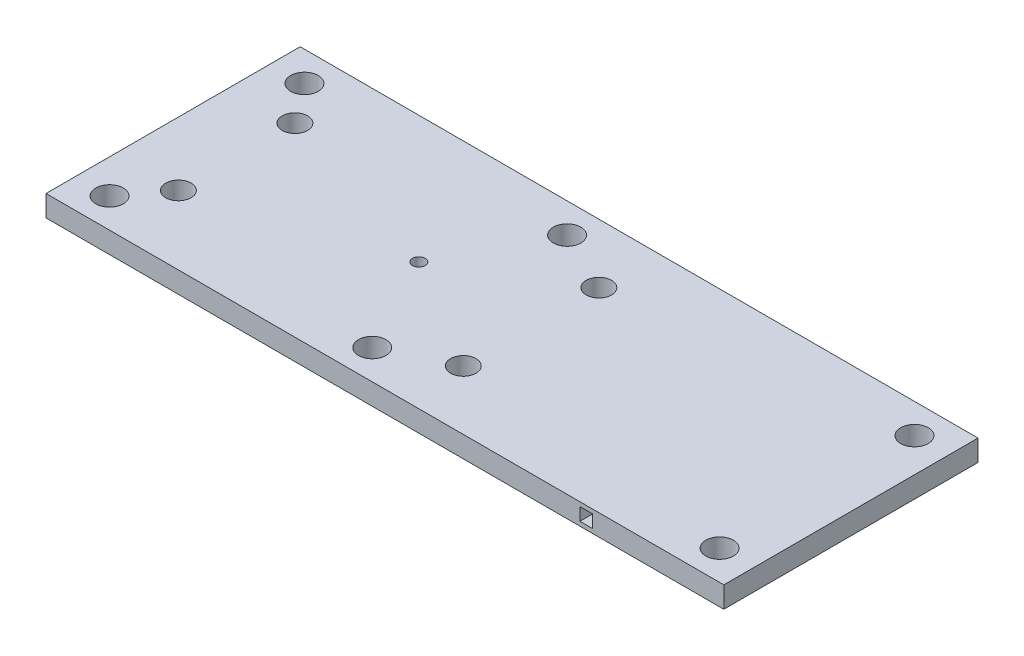
SolidWorks part; units mm, degrees
ref_plane "Front Plane" through (0, 0, 0) normal (0, 0, 1) x (1, 0, 0)
ref_plane "Top Plane" through (0, 0, 0) normal (0, 1, 0) x (1, 0, 0)
ref_plane "Right Plane" through (0, 0, 0) normal (1, 0, 0) x (0, 0, -1)
sketch "Sketch1" plane through (0, 0, 0) normal (0, 1, 0) x (1, 0, 0)
  line L1 (-80, -30) -> (80, -30)
  line L2 (-80, -30) -> (-80, 30)
  line L3 (-80, 30) -> (80, 30)
  line L4 (80, -30) -> (80, 30)
  line L5 (-80, -30) -> (80, 30) construction
  line L6 (-80, 30) -> (80, -30) construction
  circle A0 centre (-72, 23) radius 3.25
  circle A1 centre (-72, -23) radius 3.25
  circle A2 centre (72, 23) radius 3.25
  circle A3 centre (72, -23) radius 3.25
  circle A4 centre (-10, 23) radius 3.25
  circle A5 centre (-10, -23) radius 3.25
  circle A6 centre (4.5, 16) radius 3
  circle A7 centre (4.5, -16) radius 3
  circle A8 centre (-65, 13.75) radius 3
  circle A9 centre (-65, -13.75) radius 3
  circle A10 centre (-22, 0) radius 1.5
  point P0 (0, 0)
  dimension "D2" = 8
  dimension "D3" = 6.5
  dimension "D7" = 6
  dimension "D14" = 3
  dimension "D1" = 160
  dimension "60" = 60
  dimension "7" = 7
  dimension "D4" = 7
  dimension "D5" = 8
  dimension "D6" = 70
  dimension "D8" = 16.25
  dimension "D9" = 15
  dimension "D10" = 16.25
  dimension "D11" = 84.5
  dimension "D12" = 14
  dimension "D13" = 14
  dimension "D15" = 58
  dimension "D16" = 30
extrude "Boss-Extrude1" add sketch "Sketch1" along normal blind 5
sketch "Sketch2" plane through (0, 0, 30) normal (0, 0, 1) x (1, 0, 0)
  line L0 (-80, 5) -> (80, 5) construction
  line L1 (46.0306, 4) -> (49.0306, 4)
  line L2 (46.0306, 4) -> (46.0306, 1)
  line L3 (46.0306, 1) -> (49.0306, 1)
  line L4 (49.0306, 4) -> (49.0306, 1)
  line L5 (46.0306, 4) -> (49.0306, 1) construction
  line L6 (46.0306, 1) -> (49.0306, 4) construction
  point P0 (47.5306, 2.5)
  dimension "D1" = 3
  dimension "D2" = 1
extrude "Cut-1Extrude1" cut sketch "Sketch2" against normal blind 65
